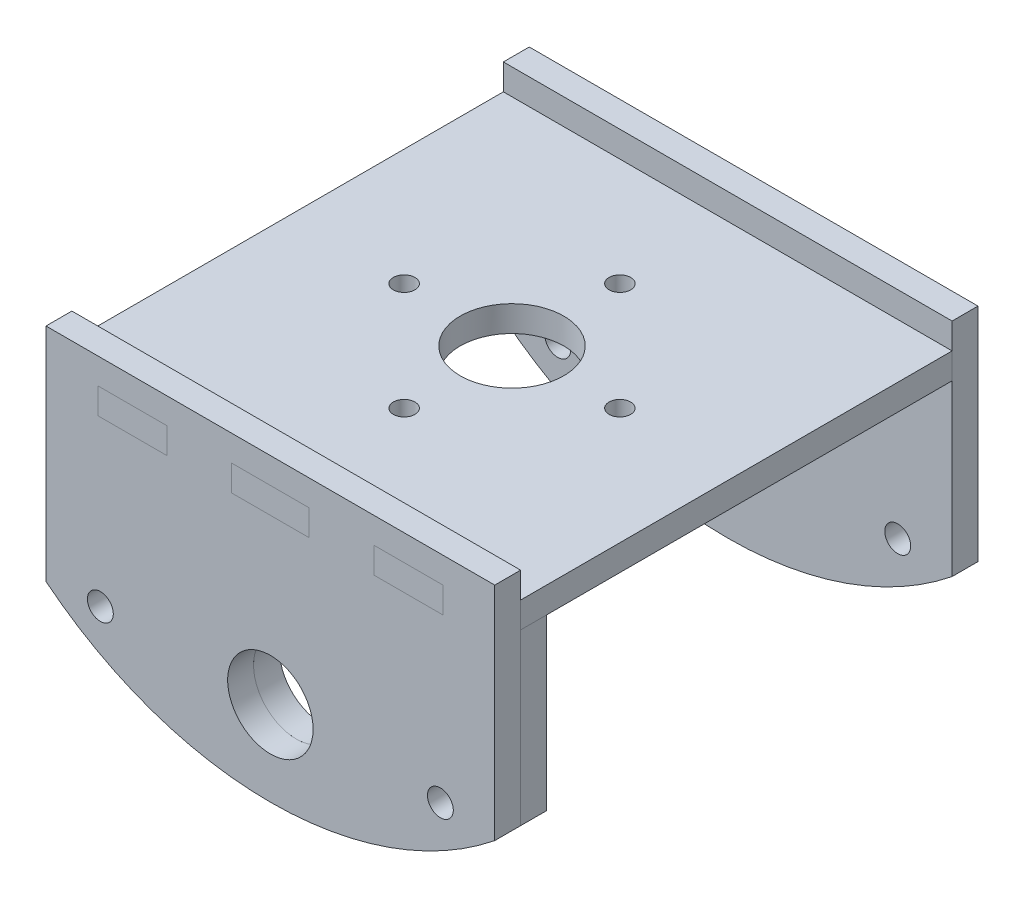
SolidWorks part; units mm, degrees
material "槭木"
ref_plane "前视基准面" through (0, 0, 0) normal (0, 0, 1) x (1, 0, 0)
ref_plane "上视基准面" through (0, 0, 0) normal (0, 1, 0) x (1, 0, 0)
ref_plane "右视基准面" through (0, 0, 0) normal (1, 0, 0) x (0, 0, -1)
sketch "草图1" plane through (0, 0, 0) normal (0, 0, 1) x (1, 0, 0)
  line L0 (0, 0) -> (39.4, 0) construction
  line L1 (-5.3, 0) -> (44.7, 0) construction
  line L2 (-5.3, 6) -> (44.7, 6)
  line L3 (-5.3, -6) -> (44.7, -6)
  circle A0 centre (0, 0) radius 1.5
  circle A1 centre (39.4, 0) radius 1.5
  arc A2 (-5.3, 6) -> (-5.3, -6) centre (-5.3, 0) ccw
  arc A3 (44.7, -6) -> (44.7, 6) centre (44.7, 0) ccw
  circle A4 centre (19.7, 0) radius 2.5
  point P7 (19.7, 0)
  dimension "D1" = 3
  dimension "D2" = 3
  dimension "D6" = 5
  dimension "D3" = 39.4
  dimension "D4" = 50
  dimension "D5" = 12
extrude "凸台-拉伸1" add sketch "草图1" along normal blind 3
sketch "草图2" plane through (0, 0, 3) normal (0, 0, 1) x (1, 0, 0)
  line L0 (44.7, 6) -> (-5.3, 6) construction
  line L2 (-11.3, -15) -> (-11.3, 15)
  line L3 (-11.3, 15) -> (50.7, 15)
  line L4 (50.7, -15) -> (50.7, 15)
  line L5 (44.7, 6) -> (-5.3, 6)
  line L7 (44.7, -6) -> (-5.3, -6)
  line L8 (-11.3, -15) -> (50.7, -15)
  arc A0 (-5.3, 6) -> (-5.3, -6) centre (-5.3, 0) ccw construction
  arc A1 (44.7, -6) -> (44.7, 6) centre (44.7, 0) ccw construction
  arc A2 (44.7, -6) -> (44.7, 6) centre (44.7, 0) ccw
  arc A3 (-5.3, 6) -> (-5.3, -6) centre (-5.3, 0) ccw
  circle A4 centre (39.4, 0) radius 1.5 construction
  circle A5 centre (19.7, 0) radius 2.5 construction
  circle A6 centre (0, 0) radius 1.5 construction
  circle A7 centre (39.4, 0) radius 1.5
  circle A8 centre (19.7, 0) radius 2.5
  circle A9 centre (0, 0) radius 1.5
  point P12 (50.7, 0)
  circle M5 centre (39.4, 0) radius 1.5
  arc M6 (-5.3, 6) -> (-5.3, -6) centre (-5.3, 0) ccw
  line M7 (-5.3, -6) -> (44.7, -6)
  arc M8 (44.7, -6) -> (44.7, 6) centre (44.7, 0) ccw
  line M9 (44.7, 6) -> (-5.3, 6)
  circle M10 centre (0, 0) radius 1.5
  circle M11 centre (19.7, 0) radius 2.5
extrude "凸台-拉伸6" add sketch "草图2" against normal blind 5 contours L4 L3 L2 M8 M6 M9 | M9 M6 M7 M8 M11 M10 M5 | L2 L8 L4 M8 M7 M6
sketch "草图5" plane through (0, 0, -2) normal (0, 0, -1) x (-1, 0, 0)
  line L4 (11.3, -15) -> (11.3, 15)
  line L5 (11.3, 15) -> (-50.7, 15)
  line L6 (-50.7, 15) -> (-50.7, -15)
  line L7 (-50.7, -15) -> (11.3, -15)
  line L8 (11.3, -15) -> (11.3, 15)
  line L9 (11.3, 15) -> (-50.7, 15)
  line L10 (-50.7, 15) -> (-50.7, -15)
  line L11 (-50.7, -15) -> (11.3, -15)
  dimension "D1" = 0
extrude "切除-拉伸1" cut sketch "草图5" against normal blind 2
sketch "草图6" plane through (0, 0, 0) normal (0, 0, -1) x (-1, 0, 0)
  line L0 (-50.7, 15) -> (-50.7, -15) construction
  line L1 (-42.7, 9) -> (-32.7, 9)
  line L2 (-42.7, 9) -> (-42.7, 12)
  line L3 (-42.7, 12) -> (-32.7, 12)
  line L4 (-32.7, 9) -> (-32.7, 12)
  line L5 (-42.7, 9) -> (-32.7, 12) construction
  line L6 (-42.7, 12) -> (-32.7, 9) construction
  line L7 (-24.7, 9) -> (-14.7, 9)
  line L8 (-24.7, 9) -> (-24.7, 12)
  line L9 (-24.7, 12) -> (-14.7, 12)
  line L10 (-14.7, 9) -> (-14.7, 12)
  line L11 (-24.7, 9) -> (-14.7, 12) construction
  line L12 (-24.7, 12) -> (-14.7, 9) construction
  line L13 (-6.7, 9) -> (3.3, 9)
  line L14 (-6.7, 9) -> (-6.7, 12)
  line L15 (-6.7, 12) -> (3.3, 12)
  line L16 (3.3, 9) -> (3.3, 12)
  line L17 (-6.7, 9) -> (3.3, 12) construction
  line L18 (-6.7, 12) -> (3.3, 9) construction
  line L19 (11.3, -15) -> (11.3, 15) construction
  line L20 (11.3, 15) -> (-50.7, 15) construction
  point P0 (-37.7, 10.5)
  point P7 (-19.7, 10.5)
  point P12 (-1.7, 10.5)
  dimension "D1" = 10
  dimension "D2" = 10
  dimension "D3" = 10
  dimension "D4" = 8
  dimension "D5" = 8
  dimension "D6" = 3
  dimension "D7" = 3
  dimension "D8" = 3
  dimension "D9" = 8
  dimension "D10" = 8
  dimension "D11" = 3
  dimension "D12" = 3
  dimension "D13" = 3
extrude "切除-拉伸2" cut sketch "草图6" against normal blind 10
sketch "草图7" plane through (0, 9, 0) normal (0, 1, 0) x (1, 0, 0)
  line L0 (42.7, -3) -> (42.7, 0)
  line L1 (42.7, 0) -> (32.7, 0)
  line L2 (32.7, 0) -> (32.7, -3)
  line L3 (32.7, -3) -> (24.7, -3)
  line L4 (24.7, -3) -> (24.7, 0)
  line L5 (24.7, 0) -> (14.7, 0)
  line L6 (14.7, 0) -> (14.7, -3)
  line L7 (14.7, -3) -> (6.7, -3)
  line L8 (6.7, -3) -> (6.7, 0.0628)
  line L9 (6.7, 0.0628) -> (-3.3, 0)
  line L10 (-3.3, 0) -> (-3.3, -3)
  line L11 (-3.3, -3) -> (-11.3, -3)
  line L12 (42.7, -3) -> (50.7, -3)
  line L13 (-11.3, -3) -> (-11.3, -53)
  line L14 (-11.3, -53) -> (50.7, -53)
  line L15 (50.7, -3) -> (50.7, -53)
  dimension "D1" = 50
sketch "草图8" plane through (0, 0, 3) normal (0, 0, 1) x (1, 0, 0)
  line L0 (-11.3, -15) -> (50.7, -15) construction
  line L1 (-11.3, 15) -> (-6.3, 15)
  line L2 (-11.3, 15) -> (-11.3, -15)
  line L3 (-11.3, -15) -> (-6.3, -15)
  line L4 (-6.3, 15) -> (-6.3, -15)
  line L6 (50.7, 15) -> (45.7, 15)
  line L7 (50.7, 15) -> (50.7, -15)
  line L8 (50.7, -15) -> (45.7, -15)
  line L9 (45.7, 15) -> (45.7, -15)
  dimension "D1" = 5
  dimension "D2" = 5
extrude "切除-拉伸3" cut sketch "草图8" against normal blind 13
pattern_linear "阵列(线性)1" count 2 spacing 61 along (0, 0, 1) of bodies 113
sketch "草图9" plane through (0, 9, 0) normal (0, 1, 0) x (1, 0, 0)
  line L1 (-3.3, 0) -> (-3.3, -3) construction
  line L2 (6.7, 0.0628) -> (-3.3, 0) construction
  line L3 (6.7, -3) -> (6.7, 0.0628) construction
  line L4 (14.7, -3) -> (6.7, -3) construction
  line L5 (14.7, 0) -> (14.7, -3) construction
  line L6 (24.7, 0) -> (14.7, 0) construction
  line L7 (24.7, -3) -> (24.7, 0) construction
  line L8 (32.7, -3) -> (24.7, -3) construction
  line L9 (32.7, 0) -> (32.7, -3) construction
  line L10 (42.7, 0) -> (32.7, 0) construction
  line L11 (42.7, -3) -> (42.7, 0) construction
  line L15 (-3.3, -3) -> (-6.3, -3)
  line L16 (-3.3, 0) -> (-3.3, -3)
  line L17 (6.7, 0.0628) -> (-3.3, 0)
  line L18 (6.7, -3) -> (6.7, 0.0628)
  line L19 (14.7, -3) -> (6.7, -3)
  line L20 (14.7, 0) -> (14.7, -3)
  line L21 (24.7, 0) -> (14.7, 0)
  line L22 (24.7, -3) -> (24.7, 0)
  line L23 (32.7, -3) -> (24.7, -3)
  line L24 (32.7, 0) -> (32.7, -3)
  line L25 (42.7, 0) -> (32.7, 0)
  line L26 (42.7, -3) -> (42.7, 0)
  line L27 (42.7, -3) -> (45.7, -3)
  line L28 (-6.3, -3) -> (-6.3, -61)
  line L30 (42.7, -61) -> (45.7, -61)
  line L31 (42.7, -61) -> (42.7, -64)
  line L32 (42.7, -64) -> (32.7, -64)
  line L33 (32.7, -64) -> (32.7, -61)
  line L34 (32.7, -61) -> (24.7, -61)
  line L35 (24.7, -61) -> (24.7, -64)
  line L36 (24.7, -64) -> (14.7, -64)
  line L37 (14.7, -64) -> (14.7, -61)
  line L38 (14.7, -61) -> (6.7, -61)
  line L39 (6.7, -61) -> (6.7, -64.0628)
  line L40 (6.7, -64.0628) -> (-3.3, -64)
  line L41 (-3.3, -64) -> (-3.3, -61)
  line L42 (-3.3, -61) -> (-6.3, -61)
  line L43 (45.7, -3) -> (45.7, -61)
sketch "草图11" plane through (0, 0, 64) normal (0, 0, 1) x (1, 0, 0)
  line L0 (45.7, -11.522) -> (27.6839, -9.0819)
  line L1 (45.7, 15) -> (45.7, -15) construction
  line L2 (27.6839, -9.0819) -> (16.4859, -8.1573)
sketch "草图12" plane through (0, 0, 64) normal (0, 0, 1) x (1, 0, 0)
  line L0 (-6.3, 15) -> (45.7, 15) construction
  line L1 (45.7, 15) -> (45.7, -15) construction
  line L2 (-6.3, -15) -> (-6.3, 15) construction
  line L3 (45.7, 0.0334) -> (45.7, -15)
  line L4 (-6.3, -15) -> (-6.3, 0.0334)
  line L5 (-6.3, -15) -> (45.7, -15)
  arc A0 (-6.3, 0.0334) -> (45.7, 0.0334) centre (19.7, 15) ccw
  line M2 (-6.3, 15) -> (-6.3, -15)
  line M3 (-6.3, -15) -> (45.7, -15)
  line M4 (45.7, -15) -> (45.7, 15)
extrude "切除-拉伸9" cut sketch "草图12" against normal blind 3 contours A0 M2 M3 | A0 L5 M4
sketch "草图13" plane through (0, 0, 3) normal (0, 0, 1) x (1, 0, 0)
  line L0 (-6.3, 0.0334) -> (-24.121, -20.1116)
  line L1 (-24.121, -20.1116) -> (36.9658, -34.6693)
  line L2 (36.9658, -34.6693) -> (65.1462, -11.8323)
  line L3 (65.1462, -11.8323) -> (46.1015, -0.5879)
  arc A0 (-6.3, 0.0334) -> (45.7, 0.0334) centre (19.7, 15) ccw construction
  arc A1 (-6.3, 0.0334) -> (45.7, 0.0334) centre (19.7, 15) ccw
extrude "切除-拉伸10" cut sketch "草图13" against normal blind 3 and the other way through all
sketch "草图14" plane through (0, 9, 0) normal (0, 1, 0) x (1, 0, 0)
  line L0 (-3.3, -3) -> (6.7, -3) construction
  line L1 (6.7, -3) -> (6.7, 0) construction
  line L2 (6.7, 0) -> (-3.3, 0) construction
  line L3 (-3.3, 0) -> (-3.3, -3) construction
  line L4 (32.7, -64) -> (42.7, -64)
  line L5 (42.7, -64) -> (42.7, -61)
  line L6 (42.7, -61) -> (32.7, -61)
  line L7 (32.7, -61) -> (32.7, -64)
  line L8 (32.7, -64) -> (42.7, -64)
  line L9 (42.7, -64) -> (42.7, -61)
  line L10 (42.7, -61) -> (32.7, -61)
  line L11 (32.7, -61) -> (32.7, -64)
  line L12 (14.7, -3) -> (24.7, -3) construction
  line L13 (24.7, -3) -> (24.7, 0) construction
  line L14 (24.7, 0) -> (14.7, 0) construction
  line L15 (14.7, 0) -> (14.7, -3) construction
  line L16 (32.7, -3) -> (42.7, -3) construction
  line L17 (42.7, -3) -> (42.7, 0) construction
  line L18 (42.7, 0) -> (32.7, 0) construction
  line L19 (32.7, 0) -> (32.7, -3) construction
  line L20 (-3.3, -64) -> (6.7, -64) construction
  line L21 (6.7, -64) -> (6.7, -61) construction
  line L22 (6.7, -61) -> (-3.3, -61) construction
  line L23 (-3.3, -61) -> (-3.3, -64) construction
  line L24 (14.7, -64) -> (24.7, -64) construction
  line L25 (24.7, -64) -> (24.7, -61) construction
  line L26 (24.7, -61) -> (14.7, -61) construction
  line L27 (14.7, -61) -> (14.7, -64) construction
  line L28 (-3.3, -3) -> (6.7, -3)
  line L29 (6.7, -3) -> (6.7, 0)
  line L30 (6.7, 0) -> (-3.3, 0)
  line L31 (-3.3, 0) -> (-3.3, -3)
  line L32 (14.7, -3) -> (24.7, -3)
  line L33 (24.7, -3) -> (24.7, 0)
  line L34 (24.7, 0) -> (14.7, 0)
  line L35 (14.7, 0) -> (14.7, -3)
  line L36 (32.7, -3) -> (42.7, -3)
  line L37 (42.7, -3) -> (42.7, 0)
  line L38 (42.7, 0) -> (32.7, 0)
  line L39 (32.7, 0) -> (32.7, -3)
  line L40 (-3.3, -64) -> (6.7, -64)
  line L41 (6.7, -64) -> (6.7, -61)
  line L42 (6.7, -61) -> (-3.3, -61)
  line L43 (-3.3, -61) -> (-3.3, -64)
  line L44 (14.7, -64) -> (24.7, -64)
  line L45 (24.7, -64) -> (24.7, -61)
  line L46 (24.7, -61) -> (14.7, -61)
  line L47 (14.7, -61) -> (14.7, -64)
  dimension "D1" = 0
extrude "凸台-拉伸7" add sketch "草图14" along normal up to surface (3 mm away) up to face at (37.7, 12, 62.5)
sketch "草图16" plane through (0, 15, 0) normal (0, 1, 0) x (1, 0, 0)
  line L4 (45.7, -61) -> (-6.3, -61)
  line L5 (-6.3, -61) -> (-6.3, -64)
  line L6 (-6.3, -64) -> (45.7, -64)
  line L7 (45.7, -64) -> (45.7, -61)
  line L8 (45.7, -61) -> (-6.3, -61)
  line L9 (-6.3, -61) -> (-6.3, -64)
  line L10 (-6.3, -64) -> (45.7, -64)
  line L11 (45.7, -64) -> (45.7, -61)
  dimension "D1" = 0
extrude "凸台-拉伸8" add sketch "草图16" along normal blind 10
sketch "草图17" plane through (0, 15, 0) normal (0, 1, 0) x (1, 0, 0)
  line L4 (45.7, 0) -> (-6.3, 0)
  line L5 (-6.3, 0) -> (-6.3, -3)
  line L6 (-6.3, -3) -> (45.7, -3)
  line L7 (45.7, -3) -> (45.7, 0)
  line L8 (45.7, 0) -> (-6.3, 0)
  line L9 (-6.3, 0) -> (-6.3, -3)
  line L10 (-6.3, -3) -> (45.7, -3)
  line L11 (45.7, -3) -> (45.7, 0)
  dimension "D1" = 0
extrude "凸台-拉伸9" add sketch "草图17" along normal blind 10
sketch "草图18" plane through (0, 0, 0) normal (0, 0, -1) x (-1, 0, 0)
  line L0 (-45.7, 0.0334) -> (-45.7, 25) construction
  line L1 (-39.7, 19) -> (-31.7, 19)
  line L2 (-39.7, 19) -> (-39.7, 22)
  line L3 (-39.7, 22) -> (-31.7, 22)
  line L4 (-31.7, 19) -> (-31.7, 22)
  line L5 (-39.7, 19) -> (-31.7, 22) construction
  line L6 (-39.7, 22) -> (-31.7, 19) construction
  line L11 (-24.2, 22) -> (-15.2, 22)
  line L12 (-24.2, 22) -> (-24.2, 19)
  line L13 (-24.2, 19) -> (-15.2, 19)
  line L14 (-15.2, 22) -> (-15.2, 19)
  line L15 (-7.7, 22) -> (0.3, 22)
  line L16 (-7.7, 22) -> (-7.7, 19)
  line L17 (-7.7, 19) -> (0.3, 19)
  line L18 (0.3, 22) -> (0.3, 19)
  line L19 (6.3, 25) -> (6.3, 0.0334) construction
  line L20 (-45.7, 25) -> (6.3, 25) construction
  point P0 (-35.7, 20.5)
  point P5 (-23.1538, 22.0555)
  dimension "D1" = 3
  dimension "D2" = 3
  dimension "D3" = 3
  dimension "D4" = 8
  dimension "D5" = 9
  dimension "D6" = 8
  dimension "D7" = 6
  dimension "D8" = 6
  dimension "D9" = 7.5
  dimension "D10" = 3
  dimension "D11" = 3
  dimension "D12" = 3
extrude "切除-拉伸11" cut sketch "草图18" against normal blind 92
sketch "草图19" plane through (0, 19, 0) normal (0, 1, 0) x (1, 0, 0)
  line L0 (39.7, -3) -> (39.7, 0)
  line L1 (39.7, 0) -> (31.7, 0)
  line L2 (31.7, 0) -> (31.7, -3)
  line L3 (31.7, -3) -> (24.2, -3)
  line L4 (24.2, -3) -> (24.2, 0)
  line L5 (24.2, 0) -> (15.2, 0)
  line L6 (15.2, 0) -> (15.2, -3)
  line L7 (15.2, -3) -> (7.7, -3)
  line L8 (7.7, -3) -> (7.7, 0)
  line L9 (7.7, 0) -> (-0.3, 0)
  line L10 (-0.3, 0) -> (-0.3, -3)
  line L11 (-0.3, -3) -> (-6.3, -3)
  line L12 (39.7, -3) -> (45.7, -3)
  line L13 (-6.3, -3) -> (-6.3, -61)
  line L15 (39.7, -61) -> (45.7, -61)
  line L16 (-0.3, -61) -> (-6.3, -61)
  line L17 (-0.3, -64) -> (-0.3, -61)
  line L18 (7.7, -64) -> (-0.3, -64)
  line L19 (7.7, -61) -> (7.7, -64)
  line L20 (15.2, -61) -> (7.7, -61)
  line L21 (15.2, -64) -> (15.2, -61)
  line L22 (24.2, -64) -> (15.2, -64)
  line L23 (24.2, -61) -> (24.2, -64)
  line L24 (31.7, -61) -> (24.2, -61)
  line L25 (31.7, -64) -> (31.7, -61)
  line L26 (39.7, -64) -> (31.7, -64)
  line L27 (39.7, -61) -> (39.7, -64)
  line L28 (45.7, -3) -> (45.7, -61)
extrude "凸台-拉伸10" add sketch "草图19" along normal up to surface (3 mm away) separate body up to face at (3.7, 22, 62.5)
sketch "草图20" plane through (0, 0, 64) normal (0, 0, 1) x (1, 0, 0)
  line L0 (4.8006, 11.4765) -> (22.653, 8.8591)
sketch "草图21" plane through (0, 0, 64) normal (0, 0, 1) x (1, 0, 0)
  line L0 (-6.3, 0.0334) -> (-6.3, -7.7904)
  line L1 (-6.3, -7.7904) -> (45.7, -7.7904)
  line L2 (45.7, -7.7904) -> (45.7, 0.0334)
  line L3 (45.7, 0.0334) -> (28.4882, -6.0552)
  line L4 (28.4882, -6.0552) -> (-2.8582, -2.3048)
  line L5 (-2.8582, -2.3048) -> (-6.3, 0.0334)
extrude "凸台-拉伸11" add sketch "草图21" against normal up to surface (3 mm away)
sketch "草图22" plane through (0, -7.7904, 0) normal (0, -1, 0) x (1, 0, 0)
  line L1 (-95.4534, -42.4892) -> (91.4579, -42.4892)
  line L2 (-95.4534, -42.4892) -> (-95.4534, 167.4011)
  line L3 (-95.4534, 167.4011) -> (91.4579, 167.4011)
  line L4 (91.4579, -42.4892) -> (91.4579, 167.4011)
  line L5 (-95.4534, -42.4892) -> (91.4579, 167.4011) construction
  line L6 (-95.4534, 167.4011) -> (91.4579, -42.4892) construction
  point P0 (-1.9978, 62.4559)
extrude "切除-拉伸12" cut sketch "草图22" along normal blind 32
sketch "草图23" plane through (0, 0, 0) normal (0, 0, -1) x (-1, 0, 0)
  line L0 (-39.7, 19) -> (-31.7, 19) construction
  line L1 (-63.7, -30.5809) -> (-27.7, -30.5809)
  line L2 (-63.7, -30.5809) -> (-63.7, 15)
  line L3 (-63.7, 15) -> (-27.7, 15)
  line L4 (-27.7, -30.5809) -> (-27.7, 15)
  line L5 (-63.7, -30.5809) -> (-27.7, 15) construction
  line L6 (-63.7, 15) -> (-27.7, -30.5809) construction
  line L7 (-11.7, -30.5809) -> (24.3, -30.5809)
  line L8 (-11.7, -30.5809) -> (-11.7, 15)
  line L9 (-11.7, 15) -> (24.3, 15)
  line L10 (24.3, -30.5809) -> (24.3, 15)
  line L11 (-11.7, -30.5809) -> (24.3, 15) construction
  line L12 (-11.7, 15) -> (24.3, -30.5809) construction
  line L13 (-7.7, 19) -> (0.3, 19) construction
  line L14 (6.3, 25) -> (6.3, 0.0334) construction
  line L15 (-45.7, 0.0334) -> (-45.7, 25) construction
  point P0 (-45.7, -7.7904)
  point P6 (6.3, -7.7904)
  dimension "D1" = 4
  dimension "D2" = 4
  dimension "D3" = 18
  dimension "D4" = 18
extrude "切除-拉伸13" cut sketch "草图23" against normal blind 32
sketch "草图24" plane through (0, 22, 0) normal (0, 1, 0) x (1, 0, 0)
  circle A0 centre (19.7, -32) radius 6
  dimension "D1" = 12
extrude "切除-拉伸14" cut sketch "草图24" against normal blind 70
sketch "草图25" plane through (0, 22, 0) normal (0, 1, 0) x (1, 0, 0)
  line L0 (19.7, -20.75) -> (19.7, -32)
  line L2 (30.95, -32) -> (8.45, -32)
  arc A0 (20.9484, -44.4375) -> (32.1375, -33.2484) centre (19.7, -32) ccw
  circle A1 centre (19.7, -19.5) radius 1.25
  circle A2 centre (7.2, -32) radius 1.25
  circle A3 centre (19.7, -44.5) radius 1.25
  circle A4 centre (32.2, -32) radius 1.25
  arc A5 (32.1375, -30.7516) -> (20.9484, -19.5625) centre (19.7, -32) ccw
  arc A6 (18.4516, -19.5625) -> (7.2625, -30.7516) centre (19.7, -32) ccw
  arc A7 (7.2625, -33.2484) -> (18.4516, -44.4375) centre (19.7, -32) ccw
  dimension "D1" = 25
  dimension "D2" = 2.5
  dimension "D3" = 2.5
  dimension "D4" = 2.5
  dimension "D5" = 2.5
extrude "切除-拉伸15" cut sketch "草图25" against normal blind 70 contours A1 | A4 | A2 | A3 L0
sketch "草图26" plane through (0, 0, 64) normal (0, 0, 1) x (1, 0, 0)
  circle A0 centre (19.7, 0) radius 4.95
  dimension "D1" = 9.9
extrude "切除-拉伸16" cut sketch "草图26" against normal blind 70
sketch "草图27" plane through (11.7, 0, 0) normal (-1, 0, 0) x (0, 0, 1)
  line L4 (3, -7.7904) -> (3, 15)
  line L5 (3, 15) -> (0, 15)
  line L6 (0, 15) -> (0, -7.7904)
  line L7 (0, -7.7904) -> (3, -7.7904)
  line L8 (3, -7.7904) -> (3, 15)
  line L9 (3, 15) -> (0, 15)
  line L10 (0, 15) -> (0, -7.7904)
  line L11 (0, -7.7904) -> (3, -7.7904)
  dimension "D1" = 0
extrude "凸台-拉伸12" add sketch "草图27" along normal blind 2
sketch "草图28" plane through (27.7, 0, 0) normal (1, 0, 0) x (0, 0, -1)
  line L4 (-3, 15) -> (-3, -7.7904)
  line L5 (-3, -7.7904) -> (0, -7.7904)
  line L6 (0, -7.7904) -> (0, 15)
  line L7 (0, 15) -> (-3, 15)
  line L8 (-3, 15) -> (-3, -7.7904)
  line L9 (-3, -7.7904) -> (0, -7.7904)
  line L10 (0, -7.7904) -> (0, 15)
  line L11 (0, 15) -> (-3, 15)
  dimension "D1" = 0
extrude "凸台-拉伸13" add sketch "草图28" along normal blind 2
sketch "草图29" plane through (0, -7.7904, 0) normal (0, -1, 0) x (1, 0, 0)
  line L4 (45.7, 64) -> (-6.3, 64)
  line L5 (-6.3, 64) -> (-6.3, 61)
  line L6 (-6.3, 61) -> (45.7, 61)
  line L7 (45.7, 61) -> (45.7, 64)
  line L8 (45.7, 64) -> (-6.3, 64)
  line L9 (-6.3, 64) -> (-6.3, 61)
  line L10 (-6.3, 61) -> (45.7, 61)
  line L11 (45.7, 61) -> (45.7, 64)
  dimension "D1" = 0
extrude "凸台-拉伸14" add sketch "草图29" along normal blind 2
sketch "草图30" plane through (0, -7.7904, 0) normal (0, -1, 0) x (1, 0, 0)
  line L4 (9.7, 0) -> (29.7, 0)
  line L5 (29.7, 0) -> (29.7, 3)
  line L6 (29.7, 3) -> (9.7, 3)
  line L7 (9.7, 3) -> (9.7, 0)
  line L8 (9.7, 0) -> (29.7, 0)
  line L9 (29.7, 0) -> (29.7, 3)
  line L10 (29.7, 3) -> (9.7, 3)
  line L11 (9.7, 3) -> (9.7, 0)
  dimension "D1" = 0
extrude "凸台-拉伸15" add sketch "草图30" along normal blind 2
sketch "草图31" plane through (0, 0, 64) normal (0, 0, 1) x (1, 0, 0)
  line L2 (-6.3, -0.6462) -> (-6.3, -9.7904)
  line L3 (-6.3, -9.7904) -> (45.7, -9.7904)
  line L4 (45.7, -9.7904) -> (45.7, -0.6462)
  arc A3 (-6.3, -0.6462) -> (45.7, -0.6462) centre (19.7, 31.7449) ccw
  line M3 (-6.3, 25) -> (-6.3, -9.7904)
  line M4 (-6.3, -9.7904) -> (45.7, -9.7904)
  line M5 (45.7, -9.7904) -> (45.7, 25)
extrude "切除-拉伸18" cut sketch "草图31" against normal blind 12 contours A3 L3 M5 | A3 M3 M4
sketch "草图32" plane through (0, 0, 0) normal (0, 0, -1) x (-1, 0, 0)
  line L0 (-45.7, -0.6462) -> (-43.9503, -12.6505)
  line L1 (-43.9503, -12.6505) -> (6.3, -16.6221)
  line L2 (6.3, -16.6221) -> (6.3, -0.6462)
  arc A0 (-45.7, -0.6462) -> (6.3, -0.6462) centre (-19.7, 31.7449) ccw construction
  arc A1 (-45.7, -0.6462) -> (6.3, -0.6462) centre (-19.7, 31.7449) ccw
extrude "切除-拉伸19" cut sketch "草图32" against normal blind 12
sketch "草图33" plane through (0, 22, 0) normal (0, 1, 0) x (1, 0, 0)
  circle A0 centre (19.7, -32) radius 17.0583
extrude "凸台-拉伸16" add sketch "草图33" against normal up to surface (3 mm away) up to face at (19.7, 19, 18.25)
sketch "草图34" plane through (0, 0, 0) normal (0, 0, -1) x (-1, 0, 0)
  circle A0 centre (-20.2334, 12.4788) radius 56.3376
extrude "切除-拉伸20" cut sketch "草图34" against normal blind 7
ref_plane "基准面1" through (0, 0, 34) normal (0, 0, 1) x (1, 0, 0)
mirror "镜向1" about plane through (0, 0, 34) normal (0, 0, 1) of bodies 142
mirror "镜向2" about plane through (0, 0, 34) normal (0, 0, 1) of bodies 139
sketch "草图36" plane through (0, 0, 4) normal (0, 0, -1) x (-1, 0, 0)
  line L3 (6.3, -0.6462) -> (6.3, 25)
  line L4 (6.3, 25) -> (-45.7, 25)
  line L5 (-45.7, 25) -> (-45.7, -0.6462)
  line L6 (6.3, -0.6462) -> (6.3, 25)
  line L7 (6.3, 25) -> (-45.7, 25)
  line L8 (-45.7, 25) -> (-45.7, -0.6462)
  arc A1 (-45.7, -0.6462) -> (6.3, -0.6462) centre (-19.7, 31.7449) ccw
  arc A2 (-45.7, -0.6462) -> (6.3, -0.6462) centre (-19.7, 31.7449) ccw
  dimension "D1" = 0
extrude "切除-拉伸21" cut sketch "草图36" against normal blind 5
ref_plane "基准面2" through (0, 0, 35) normal (0, 0, -1) x (-1, 0, 0)
mirror "镜向3" about plane through (0, 0, 35) normal (0, 0, -1) of bodies 145
mirror "镜向4" about plane through (0, 0, 35) normal (0, 0, -1) of bodies 139
sketch "草图37" plane through (0, 22, 0) normal (0, 1, 0) x (1, 0, 0)
  line L0 (1.65, -35) -> (-1.65, -35) construction
  circle A0 centre (19.7, -35) radius 6
  dimension "D1" = 12
sketch "草图38" plane through (0, 0, 6) normal (0, 0, -1) x (-1, 0, 0)
  line L3 (6.3, -0.6462) -> (6.3, 25)
  line L4 (6.3, 25) -> (-45.7, 25)
  line L5 (-45.7, 25) -> (-45.7, -0.6462)
  line L6 (6.3, -0.6462) -> (6.3, 25)
  line L7 (6.3, 25) -> (-45.7, 25)
  line L8 (-45.7, 25) -> (-45.7, -0.6462)
  arc A1 (-45.7, -0.6462) -> (6.3, -0.6462) centre (-19.7, 31.7449) ccw
  arc A2 (-45.7, -0.6462) -> (6.3, -0.6462) centre (-19.7, 31.7449) ccw
  dimension "D1" = 0
extrude "切除-拉伸23" cut sketch "草图38" against normal blind 5
ref_plane "基准面3" through (0, 0, 36) normal (0, 0, 1) x (1, 0, 0)
mirror "镜向5" about plane through (0, 0, 36) normal (0, 0, 1) of bodies 149
mirror "镜向6" about plane through (0, 0, 36) normal (0, 0, 1) of bodies 139
sketch "草图39" plane through (0, 22, 0) normal (0, 1, 0) x (1, 0, 0)
  circle A0 centre (19.7, -36) radius 6
  dimension "D1" = 12
extrude "切除-拉伸24" cut sketch "草图39" against normal blind 5
sketch "草图40" plane through (0, 0, 61) normal (0, 0, -1) x (-1, 0, 0)
  line L0 (-45.7, 19) -> (6.3, 19)
  line L3 (6.3, -0.6462) -> (6.3, 25)
  line L4 (6.3, 25) -> (-45.7, 25)
  line L5 (-45.7, 25) -> (-45.7, -0.6462)
  line L6 (6.3, -0.6462) -> (6.3, 19)
  line L8 (-45.7, 19) -> (-45.7, -0.6462)
  circle A0 centre (-39.4, 0) radius 1.5 construction
  arc A1 (-45.7, -0.6462) -> (6.3, -0.6462) centre (-19.7, 31.7449) ccw
  arc A2 (-45.7, -0.6462) -> (6.3, -0.6462) centre (-19.7, 31.7449) ccw
  circle A3 centre (-19.7, 0) radius 4.95 construction
  circle A4 centre (-39.4, 0) radius 1.5
  circle A5 centre (-19.7, 0) radius 4.95
  circle A6 centre (0, 0) radius 1.5 construction
  circle A7 centre (0, 0) radius 1.5
  dimension "D1" = 0
extrude "凸台-拉伸17" add sketch "草图40" along normal blind 3 separate body
sketch "草图41" plane through (0, 22, 0) normal (0, 1, 0) x (1, 0, 0)
  circle A1 centre (19.7, -23.5) radius 1.25
  circle A2 centre (7.2, -36) radius 1.25
  circle A3 centre (19.7, -48.5) radius 1.25
  circle A4 centre (32.2, -36) radius 1.25
  dimension "D2" = 2.5
  dimension "D3" = 2.5
  dimension "D4" = 2.5
  dimension "D5" = 2.5
extrude "切除-拉伸25" cut sketch "草图41" against normal blind 3
